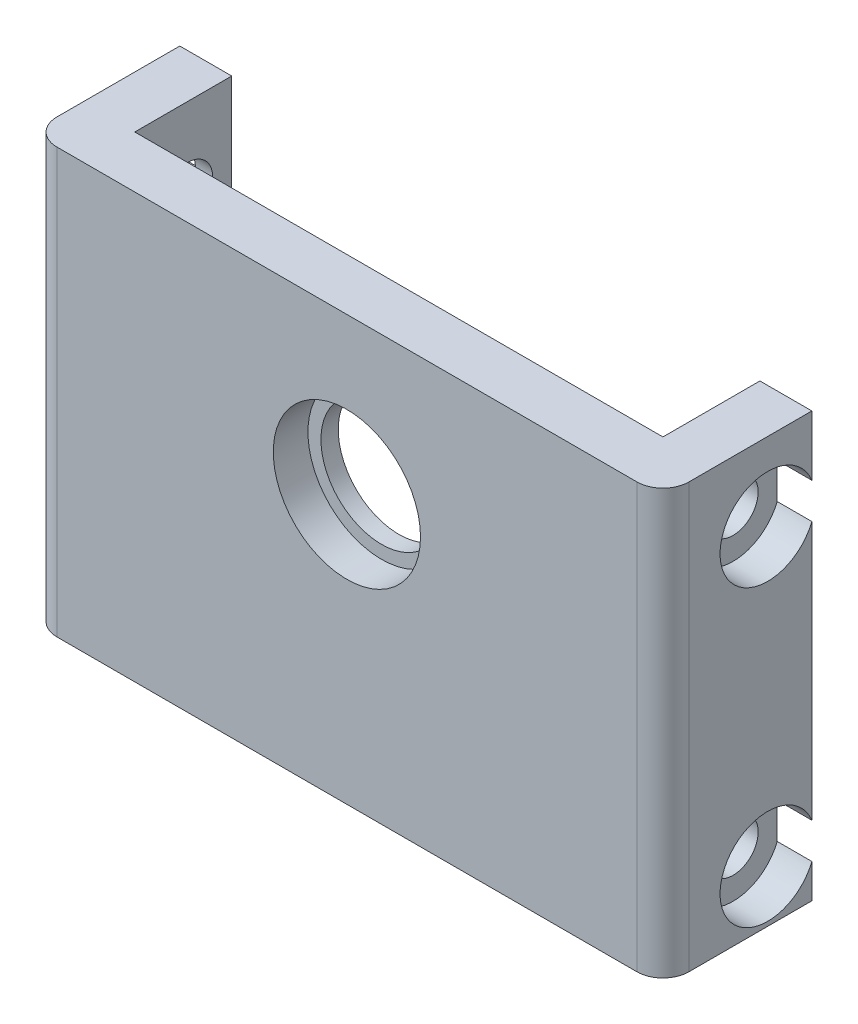
SolidWorks part; units mm, degrees
ref_plane "Plano frontal" through (0, 0, 0) normal (0, 0, 1) x (1, 0, 0)
ref_plane "Plano superior" through (0, 0, 0) normal (0, 1, 0) x (1, 0, 0)
ref_plane "Plano direito" through (0, 0, 0) normal (1, 0, 0) x (0, 0, -1)
sketch "Esboço2" plane through (0, 0, 0) normal (0, 0, 1) x (1, 0, 0)
  line L0 (2.5, -18.5) -> (4.5, -18.5) construction
  line L1 (-0.25, 3) -> (30.25, 3)
  line L2 (-0.25, 3) -> (-0.25, -21.5)
  line L3 (-0.25, -21.5) -> (30.25, -21.5)
  line L4 (30.25, 3) -> (30.25, -21.5)
  line L7 (0, -38.6) -> (0, 0) construction
  line L9 (-0.25, -1.1531) -> (0, -1.1531) construction
  line L11 (30, -1.6003) -> (30.25, -1.6003) construction
  line L12 (30, -38.6) -> (30, 0) construction
  arc A0 (18.9245, -1.4615) -> (9.4709, -3.67) centre (15, -6) ccw construction
  dimension "D1" = 9
  dimension "D2" = 0.25
  dimension "D3" = 3
extrude "Ressalto-extrusão1" add sketch "Esboço2" along normal blind 3 from offset 0.25
ref_plane "Plano1" through (15, 0, 0) normal (-1, 0, 0) x (0, 0, 1)
sketch "Esboço3" plane through (-0.25, 0, 0) normal (-1, 0, 0) x (0, 0, 1)
  line L0 (3.25, -21.5) -> (0.25, -21.5) construction
  line L1 (3.25, 3) -> (-5.35, 3)
  line L2 (3.25, 3) -> (3.25, -21.5)
  line L3 (3.25, -21.5) -> (-5.35, -21.5)
  line L4 (-5.35, 3) -> (-5.35, -21.5)
  dimension "D1" = 0.25
extrude "Ressalto-extrusão2" add sketch "Esboço3" along normal blind 3
mirror "Espelhar1" about plane through (15, 0, 0) normal (-1, 0, 0) of "Ressalto-extrusão2"
sketch "Esboço5" plane through (0, 0, 3.25) normal (0, 0, 1) x (1, 0, 0)
  circle A2 centre (15, -6) radius 4.25
  circle A3 centre (15, -6) radius 4 construction
  dimension "D1" = 0.25
extrude "Corte-extrusão1" cut sketch "Esboço5" against normal offset from surface (2 mm away) 1 up to face at (15, -9.25, 0.25)
sketch "Esboço12" plane through (0, 0, 1.25) normal (0, 0, 1) x (1, 0, 0)
  circle A2 centre (15, -6) radius 3.5
  circle A3 centre (15, -6) radius 3.25 construction
  dimension "D1" = 0.25
extrude "Corte-extrusão3" cut sketch "Esboço12" against normal through all
ref_plane "Plane1" through (15, 0, 0) normal (-1, 0, 0) x (0, 0, 1)
hole_wizard "CBORE for M2.5 SHCS1" positions "Sketch3" profile "Sketch4" counterbore size "M2.5" standard "ANSI Metric"
sketch "Sketch3" plane through (-3.25, 0, 0) normal (-1, 0, 0) x (0, 0, 1)
  circle A0 centre (-2.8, -1.5) radius 1.35 construction
  circle A1 centre (-2.8, -18.5) radius 1.35 construction
  point P0 (-2.8, -1.5)
  point P2 (-2.8, -18.5)
sketch "Sketch4" plane through (-3.25, -1.5, -2.8) normal (0, 1, 0) x (0, 0, 1)
  line L0 (0, 0) -> (0, 3)
  line L1 (0, 3) -> (1.45, 3)
  line L3 (1.45, 3) -> (1.45, 2)
  line L4 (1.45, 2) -> (2.75, 2)
  line L5 (2.75, 2) -> (2.75, 0)
  line L7 (2.75, 0) -> (0, 0)
  line L11 (0, -6.35) -> (0, 107.95) construction
  dimension "Thru Hole Dia." = 2.9
  dimension "Thru Hole Depth" = 3
  dimension "C'Bore Dia." = 5.5
  dimension "C'Bore Depth" = 2
mirror "Mirror1" about plane through (15, 0, 0) normal (-1, 0, 0) of "CBORE for M2.5 SHCS1"
fillet "Filete1" radius 1.5 2 edges at (33.25, -9.25, 3.25) (-3.25, -9.25, 3.25)
